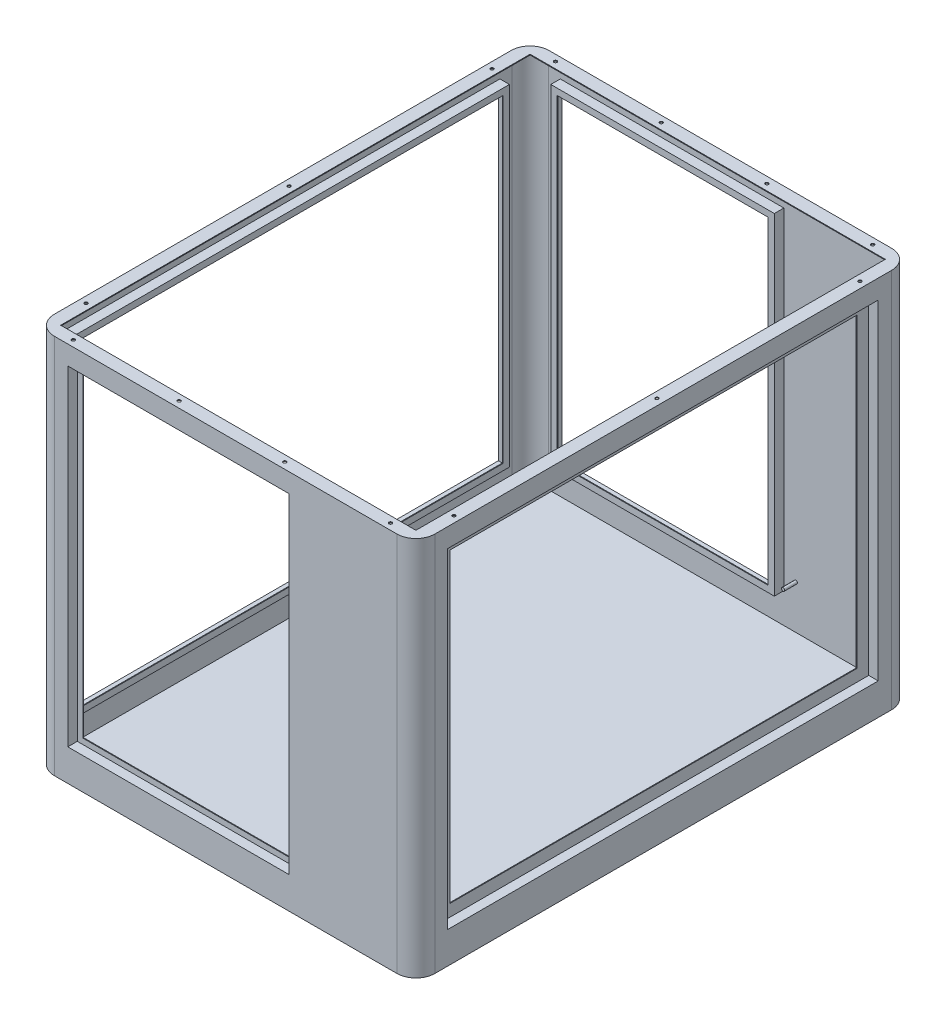
SolidWorks part; units mm, degrees
ref_plane "前视基准面" through (0, 0, 0) normal (0, 0, 1) x (1, 0, 0)
ref_plane "上视基准面" through (0, 0, 0) normal (0, 1, 0) x (1, 0, 0)
ref_plane "右视基准面" through (0, 0, 0) normal (1, 0, 0) x (0, 0, -1)
sketch "草图1" plane through (0, 0, 0) normal (0, 0, 1) x (1, 0, 0)
  line L1 (-300, -300) -> (300, -300)
  line L2 (-300, -300) -> (-300, 300)
  line L3 (-300, 300) -> (300, 300)
  line L4 (300, -300) -> (300, 300)
  line L5 (-300, -300) -> (300, 300) construction
  line L6 (-300, 300) -> (300, -300) construction
  point P0 (0, 0)
  dimension "D1" = 600
  dimension "D2" = 600
extrude "凸台-拉伸1" add sketch "草图1" along normal blind 780
fillet "圆角1" radius 30 4 edges at (-300, 0, 0) (-300, 0, 780) (300, 0, 780) (300, 0, 0)
shell "抽壳1" thickness 1.2
sketch "草图13" plane through (0, 0, 780) normal (0, 0, 1) x (1, 0, 0)
  line L0 (270, 300) -> (-270, 300) construction
  line L1 (-248.8, 270) -> (100, 270)
  line L2 (-248.8, 270) -> (-248.8, -250)
  line L3 (-248.8, -250) -> (100, -250)
  line L4 (100, 270) -> (100, -250)
  line L5 (-248.8, 270) -> (100, -250) construction
  line L6 (-248.8, -250) -> (100, 270) construction
  line L7 (300, -300) -> (300, 300) construction
  line L8 (-298.8, -298.8) -> (-298.8, 298.8) construction
  line L10 (-270, -300) -> (270, -300) construction
  point P0 (-74.4, 10)
  point P5 (0, 0)
  point P10 (0, 0)
  dimension "D1" = 30
  dimension "D2" = 200
  dimension "D3" = 50
  dimension "D4" = 50
extrude "切除-拉伸6" cut sketch "草图13" against normal blind 10
sketch "草图15" plane through (0, 0, 780) normal (0, 0, 1) x (1, 0, 0)
  line L0 (100, -250) -> (100, 270) construction
  line L1 (-248.8, -250) -> (100, -250) construction
  line L2 (-248.8, 270) -> (-248.8, -250) construction
  line L3 (100, 270) -> (-248.8, 270) construction
  line L4 (100, -250) -> (100, 270)
  line L5 (-248.8, -250) -> (100, -250)
  line L6 (-248.8, 270) -> (-248.8, -250)
  line L7 (100, 270) -> (-248.8, 270)
  line L8 (101.2, 271.2) -> (-250, 271.2)
  line L9 (-250, 271.2) -> (-250, -251.2)
  line L10 (-250, -251.2) -> (101.2, -251.2)
  line L11 (101.2, -251.2) -> (101.2, 271.2)
  dimension "D1" = 1.2
extrude "凸台-拉伸7" add sketch "草图15" against normal blind 15
sketch "草图16" plane through (0, 0, 765) normal (0, 0, -1) x (-1, 0, 0)
  line L0 (250, 271.2) -> (-101.2, 271.2) construction
  line L1 (250, 271.2) -> (-101.2, 271.2)
  line L2 (250, 271.2) -> (250, -251.2)
  line L3 (250, -251.2) -> (-101.2, -251.2)
  line L4 (-101.2, 271.2) -> (-101.2, -251.2)
  line L5 (250, -251.2) -> (250, 271.2) construction
  line L6 (240, 261.2) -> (-91.2, 261.2)
  line L7 (-91.2, 261.2) -> (-91.2, -241.2)
  line L8 (240, -241.2) -> (-91.2, -241.2)
  line L9 (240, 261.2) -> (240, -241.2)
  dimension "D1" = 10
extrude "凸台-拉伸8" add sketch "草图16" along normal blind 1.2
sketch "草图17" plane through (-300, 0, 0) normal (1, 0, 0) x (0, 0, -1)
  line L0 (-750, 300) -> (-30, 300) construction
  line L1 (-730, 270) -> (-50, 270)
  line L2 (-730, 270) -> (-730, -250)
  line L3 (-730, -250) -> (-50, -250)
  line L4 (-50, 270) -> (-50, -250)
  line L5 (-730, 270) -> (-50, -250) construction
  line L6 (-730, -250) -> (-50, 270) construction
  line L7 (-750, -300) -> (-30, -300) construction
  line L8 (0, -300) -> (0, 300) construction
  line L9 (-780, -300) -> (-780, 300) construction
  point P0 (-390, 10)
  dimension "D1" = 30
  dimension "D2" = 50
  dimension "D3" = 50
  dimension "D4" = 50
extrude "切除-拉伸7" cut sketch "草图17" along normal blind 1.2
sketch "草图19" plane through (0, 0, 0) normal (0, 0, -1) x (-1, 0, 0)
  line L0 (-270, 300) -> (270, 300) construction
  line L1 (-100, 270) -> (250, 270)
  line L2 (-100, 270) -> (-100, -250)
  line L3 (-100, -250) -> (250, -250)
  line L4 (250, 270) -> (250, -250)
  line L5 (-100, 270) -> (250, -250) construction
  line L6 (-100, -250) -> (250, 270) construction
  line L7 (300, 300) -> (300, -300) construction
  line L8 (270, -300) -> (-270, -300) construction
  line L9 (-300, -300) -> (-300, 300) construction
  point P0 (75, 10)
  point P10 (47.756, 30.8402)
  dimension "D1" = 30
  dimension "D2" = 50
  dimension "D3" = 50
  dimension "D4" = 200
extrude "切除-拉伸8" cut sketch "草图19" against normal blind 1.2
sketch "草图22" plane through (0, 0, 0) normal (0, 0, -1) x (-1, 0, 0)
  line L0 (-101.2, 271.2) -> (251.2, 271.2)
  line L1 (-100, 270) -> (250, 270)
  line L2 (-100, 270) -> (-100, -250)
  line L3 (-100, -250) -> (250, -250)
  line L4 (250, 270) -> (250, -250)
  line L5 (251.2, 271.2) -> (251.2, -251.2)
  line L6 (-101.2, -251.2) -> (251.2, -251.2)
  line L7 (-101.2, 271.2) -> (-101.2, -251.2)
  dimension "D1" = 1.2
extrude "凸台-拉伸9" add sketch "草图22" against normal blind 15
sketch "草图23" plane through (0, 0, 15) normal (0, 0, 1) x (1, 0, 0)
  line L0 (-241.2, 261.2) -> (91.2, 261.2)
  line L1 (-251.2, 271.2) -> (101.2, 271.2)
  line L2 (-251.2, 271.2) -> (-251.2, -251.2)
  line L3 (-251.2, -251.2) -> (101.2, -251.2)
  line L4 (101.2, 271.2) -> (101.2, -251.2)
  line L5 (91.2, 261.2) -> (91.2, -241.2)
  line L6 (-241.2, -241.2) -> (91.2, -241.2)
  line L7 (-241.2, 261.2) -> (-241.2, -241.2)
  dimension "D1" = 10
extrude "凸台-拉伸10" add sketch "草图23" along normal blind 1.2
sketch "草图24" plane through (-300, 0, 0) normal (1, 0, 0) x (0, 0, -1)
  line L1 (-730, 270) -> (-50, 270)
  line L2 (-730, 270) -> (-730, -250)
  line L3 (-730, -250) -> (-50, -250)
  line L4 (-50, 270) -> (-50, -250)
  line L5 (-731.2, 271.2) -> (-48.8, 271.2)
  line L6 (-48.8, 271.2) -> (-48.8, -251.2)
  line L7 (-731.2, -251.2) -> (-48.8, -251.2)
  line L8 (-731.2, 271.2) -> (-731.2, -251.2)
  dimension "D1" = 1.2
extrude "凸台-拉伸11" add sketch "草图24" along normal blind 15
sketch "草图26" plane through (-285, 0, 0) normal (1, 0, 0) x (0, 0, -1)
  line L0 (-58.8, -241.2) -> (-721.2, -241.2)
  line L1 (-48.8, 271.2) -> (-731.2, 271.2)
  line L2 (-48.8, 271.2) -> (-48.8, -251.2)
  line L3 (-48.8, -251.2) -> (-731.2, -251.2)
  line L4 (-731.2, 271.2) -> (-731.2, -251.2)
  line L5 (-721.2, 261.2) -> (-721.2, -241.2)
  line L6 (-58.8, 261.2) -> (-721.2, 261.2)
  line L7 (-58.8, 261.2) -> (-58.8, -241.2)
  dimension "D1" = 10
extrude "凸台-拉伸12" add sketch "草图26" along normal blind 1.2
sketch "草图27" plane through (0, 300, 0) normal (0, 1, 0) x (1, 0, 0)
  line L0 (270, -780) -> (-270, -780) construction
  line L1 (280, -760) -> (-280, -760)
  line L2 (280, -760) -> (280, -20)
  line L3 (280, -20) -> (-280, -20)
  line L4 (-280, -760) -> (-280, -20)
  line L5 (280, -760) -> (-280, -20) construction
  line L6 (280, -20) -> (-280, -760) construction
  line L7 (270, 0) -> (-270, 0) construction
  line L8 (-300, -750) -> (-300, -30) construction
  line L9 (300, -750) -> (300, -30) construction
  point P0 (0, -390)
  dimension "D1" = 20
  dimension "D2" = 20
  dimension "D3" = 20
  dimension "D4" = 20
extrude "切除-拉伸9" cut sketch "草图27" against normal blind 10
hole_wizard "M6 螺纹孔1" positions "草图28" profile "草图29" tap size "M6" standard "GB"
sketch "草图28" plane through (0, 300, 0) normal (0, 1, 0) x (1, 0, 0)
  line L0 (-280, -760) -> (280, -760) construction
  line L1 (300, -750) -> (300, -30) construction
  point P0 (250, -770)
  dimension "D1" = 10
  dimension "D2" = 50
sketch "草图29" plane through (250, 300, 770) normal (1, 0, 0) x (0, 0, 1)
  line L0 (0, 0) -> (0, 16.5022)
  line L1 (0, 16.5022) -> (2.5, 15)
  line L2 (2.5, 15) -> (2.5, 0)
  line L5 (2.5, 0) -> (0, 0)
  line L10 (0, 16.5022) -> (-2.5, 15) construction
  line L11 (0, -6.35) -> (0, 107.95) construction
  dimension "螺纹孔钻头直径" = 5
  dimension "螺纹孔钻头深度" = 15
  dimension "导头角度" = 118
cosmetic thread "孔螺蚊线1" parameters "D1"=1.2, "D2"=6
pattern_linear "阵列(线性)1" count 4 spacing 166.6667 along (-1, 0, 0) of "M6 螺纹孔1"
ref_plane "基准面1" through (0, 0, 390) normal (0, 0, -1) x (-1, 0, 0)
mirror "镜向1" about plane through (0, 0, 390) normal (0, 0, -1) of "阵列(线性)1", "M6 螺纹孔1"
hole_wizard "M6 螺纹孔2" positions "草图30" profile "草图31" tap size "M6" standard "GB"
sketch "草图30" plane through (0, 300, 0) normal (0, 1, 0) x (1, 0, 0)
  line L0 (270, -780) -> (-270, -780) construction
  line L1 (270, 0) -> (-270, 0) construction
  line L2 (280, -760) -> (280, -20) construction
  line L3 (300, -750) -> (300, -30) construction
  point P0 (290, -710)
  point P2 (290, -390)
  point P4 (290, -70)
  point P17 (300, -390)
  dimension "D1" = 70
  dimension "D2" = 70
  dimension "D3" = 10
sketch "草图31" plane through (290, 300, 710) normal (1, 0, 0) x (0, 0, 1)
  line L0 (0, 0) -> (0, 16.5022)
  line L1 (0, 16.5022) -> (2.5, 15)
  line L2 (2.5, 15) -> (2.5, 0)
  line L5 (2.5, 0) -> (0, 0)
  line L10 (0, 16.5022) -> (-2.5, 15) construction
  line L11 (0, -6.35) -> (0, 107.95) construction
  dimension "螺纹孔钻头直径" = 5
  dimension "螺纹孔钻头深度" = 15
  dimension "导头角度" = 118
cosmetic thread "孔螺蚊线2" parameters "D1"=1.2, "D2"=6
cosmetic thread "孔螺蚊线3" parameters "D1"=1.2, "D2"=6
cosmetic thread "孔螺蚊线4" parameters "D1"=1.2, "D2"=6
mirror "镜向2" about plane through (0, 0, 0) normal (1, 0, 0) of "M6 螺纹孔2"
mirror "镜向3" about plane through (0, 0, 0) normal (1, 0, 0) of "M6 螺纹孔2"
sketch "草图32" plane through (300, 0, 0) normal (1, 0, 0) x (0, 0, -1)
  line L0 (-750, 300) -> (-30, 300) construction
  line L1 (-730, 270) -> (-51.2, 270)
  line L2 (-730, 270) -> (-730, -250)
  line L3 (-730, -250) -> (-51.2, -250)
  line L4 (-51.2, 270) -> (-51.2, -250)
  line L5 (-730, 270) -> (-51.2, -250) construction
  line L6 (-730, -250) -> (-51.2, 270) construction
  line L7 (-1.2, 298.8) -> (-1.2, -298.8) construction
  line L8 (-780, -300) -> (-780, 300) construction
  line L9 (-750, -300) -> (-30, -300) construction
  point P0 (-390.6, 10)
  dimension "D1" = 30
  dimension "D2" = 50
  dimension "D3" = 50
  dimension "D4" = 50
extrude "切除-拉伸10" cut sketch "草图32" against normal blind 10
sketch "草图33" plane through (300, 0, 0) normal (1, 0, 0) x (0, 0, -1)
  line L0 (-731.2, 271.2) -> (-50, 271.2)
  line L1 (-730, 270) -> (-51.2, 270)
  line L2 (-730, 270) -> (-730, -250)
  line L3 (-730, -250) -> (-51.2, -250)
  line L4 (-51.2, 270) -> (-51.2, -250)
  line L5 (-50, 271.2) -> (-50, -251.2)
  line L6 (-731.2, -251.2) -> (-50, -251.2)
  line L7 (-731.2, 271.2) -> (-731.2, -251.2)
  dimension "D1" = 1.2
extrude "凸台-拉伸13" add sketch "草图33" against normal blind 15
sketch "草图34" plane through (285, 0, 0) normal (-1, 0, 0) x (0, 0, 1)
  line L0 (731.2, -251.2) -> (50, -251.2) construction
  line L1 (50, 271.2) -> (731.2, 271.2)
  line L2 (50, 271.2) -> (50, -251.2)
  line L3 (50, -251.2) -> (731.2, -251.2)
  line L4 (731.2, 271.2) -> (731.2, -251.2)
  line L5 (731.2, 271.2) -> (731.2, -251.2) construction
  line L6 (70, 251.2) -> (711.2, 251.2)
  line L7 (711.2, 251.2) -> (711.2, -231.2)
  line L8 (70, -231.2) -> (711.2, -231.2)
  line L9 (70, 251.2) -> (70, -231.2)
  dimension "D1" = 20
extrude "凸台-拉伸14" add sketch "草图34" along normal blind 1.2
sketch "草图35" plane through (0, 0, 778.8) normal (0, 0, -1) x (-1, 0, 0)
  line L0 (-270, -298.8) -> (-270, 298.8) construction
  line L1 (-270, 300) -> (270, 300) construction
  circle A0 centre (-120, 120) radius 2.5
  circle A1 centre (-120, -230) radius 2.5
  point P9 (-154.9683, -200)
  dimension "D1" = 5
  dimension "D2" = 150
  dimension "D3" = 180
  dimension "D4" = 350
extrude "凸台-拉伸15" add sketch "草图35" along normal blind 20
sketch "草图36" plane through (0, 0, 1.2) normal (0, 0, 1) x (1, 0, 0)
  circle A0 centre (120, 120) radius 2.5
  circle A1 centre (120, -230) radius 2.5
  circle A2 centre (120, 120) radius 2.5 construction
  circle A3 centre (120, -230) radius 2.5 construction
  dimension "D1" = 5
extrude "凸台-拉伸16" add sketch "草图36" along normal blind 20
